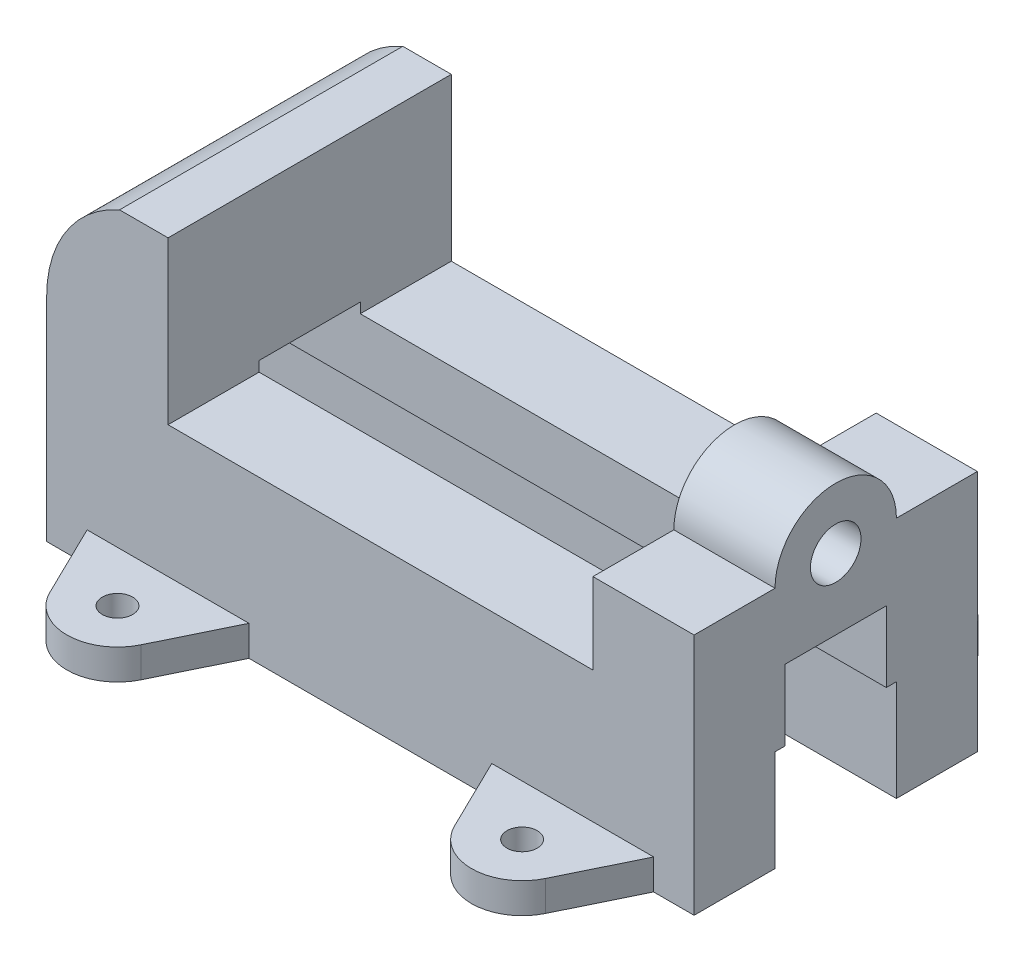
SolidWorks part; units mm, degrees
material "Gray Cast Iron"
ref_plane "Front Plane" through (0, 0, 0) normal (0, 0, 1) x (1, 0, 0)
ref_plane "Top Plane" through (0, 0, 0) normal (0, 1, 0) x (1, 0, 0)
ref_plane "Right Plane" through (0, 0, 0) normal (1, 0, 0) x (0, 0, -1)
sketch "Sketch1" plane through (0, 0, 0) normal (0, 0, 1) x (1, 0, 0)
  line L0 (0, 0) -> (0, 66.675)
  line L1 (0, 0) -> (203.2, 0)
  line L2 (203.2, 0) -> (203.2, 76.2)
  line L3 (203.2, 76.2) -> (171.45, 76.2)
  line L4 (171.45, 76.2) -> (171.45, 50.8)
  line L5 (171.45, 50.8) -> (38.1, 50.8)
  line L7 (38.1, 101.6) -> (38.1, 50.8)
  line L8 (22.8732, 101.6) -> (38.1, 101.6)
  arc A0 (0, 66.675) -> (22.8732, 101.6) centre (38.1, 66.675) cw
  point P10 (38.1, 66.675)
  point P12 (0, 0)
  dimension "D2" = 38.1
  dimension "D1" = 76.2
  dimension "D3" = 50.8
  dimension "D4" = 50.8
  dimension "D5" = 66.675
  dimension "D6" = 133.35
  dimension "D7" = 31.75
extrude "Boss-Extrude1" add sketch "Sketch1" against normal blind 88.9
sketch "Sketch2" plane through (203.2, 0, 0) normal (1, 0, 0) x (0, 0, -1)
  line L0 (88.9, 76.2) -> (0, 76.2) construction
  line L1 (25.4, 76.2) -> (63.5, 76.2)
  arc A0 (63.5, 76.2) -> (25.4, 76.2) centre (44.45, 76.2) ccw
extrude "Boss-Extrude2" add sketch "Sketch2" against normal blind 31.75
sketch "Sketch3" plane through (203.2, 0, 0) normal (1, 0, 0) x (0, 0, -1)
  circle A0 centre (44.45, 76.2) radius 7.9375
  dimension "D1" = 15.875
extrude "Cut-Extrude1" cut sketch "Sketch3" against normal blind 31.75
sketch "Sketch4" plane through (203.2, 0, 0) normal (1, 0, 0) x (0, 0, -1)
  line L0 (63.5, 0) -> (88.9, 0)
  line L1 (88.9, 0) -> (0, 0) construction
  line L4 (25.4, 0) -> (63.5, 0)
  line L5 (63.5, 31.75) -> (60.325, 31.75)
  line L6 (60.325, 31.75) -> (60.325, 53.975)
  line L7 (25.4, 0) -> (25.4, 31.75)
  line L8 (25.4, 31.75) -> (28.575, 31.75)
  line L9 (28.575, 31.75) -> (28.575, 53.975)
  line L10 (28.575, 53.975) -> (60.325, 53.975)
  line L11 (63.5, 31.75) -> (63.5, 0)
  line M14 (0, 0) -> (88.9, 0)
  dimension "D1" = 38.1
  dimension "D2" = 31.75
  dimension "D3" = 31.75
  dimension "D4" = 31.75
  dimension "D5" = 25.4
  dimension "D6" = 3.175
  dimension "D7" = 22.225
extrude "Cut-Extrude2" cut sketch "Sketch4" against normal through all contours L11 L5 L6 L10 L9 L8 L7 M14
sketch "Sketch5" plane through (0, 0, 0) normal (0, 0, 1) x (1, 0, 0)
  line L0 (0, 0) -> (12.7, 0)
  line L1 (0, 0) -> (203.2, 0) construction
  line L2 (12.7, 0) -> (12.7, 9.525)
  line L3 (12.7, 9.525) -> (63.5, 9.525)
  line L4 (63.5, 9.525) -> (63.5, 0)
  line L5 (63.5, 0) -> (12.7, 0)
  line L6 (203.2, 0) -> (190.5, 0)
  line L7 (190.5, 0) -> (190.5, 9.525)
  line L8 (190.5, 9.525) -> (139.7, 9.525)
  line L9 (139.7, 9.525) -> (139.7, 0)
  line L10 (139.7, 0) -> (190.5, 0)
  line L11 (0, 66.675) -> (0, 0) construction
  line M8 (0, 0) -> (203.2, 0)
  dimension "D1" = 12.7
  dimension "D2" = 50.8
  dimension "D3" = 9.525
  dimension "D4" = 9.525
  dimension "D5" = 50.8
  dimension "D6" = 12.7
extrude "Boss-Extrude3" add sketch "Sketch5" along normal blind 15.875 contours L4 L3 L2 M8 | L8 L9 L7 M8
sketch "Sketch7" plane through (0, 9.525, 0) normal (0, 1, 0) x (1, 0, 0)
  line L0 (12.7, -15.875) -> (63.5, -15.875) construction
  line L1 (12.7, 0) -> (23.8303, -22.8315)
  line L2 (63.5, 0) -> (52.3697, -22.8315)
  line L3 (12.7, 0) -> (63.5, 0)
  arc A0 (23.8303, -22.8315) -> (52.3697, -22.8315) centre (38.1, -15.875) ccw
  dimension "D1" = 31.75
extrude "Boss-Extrude4" add sketch "Sketch7" against normal blind 9.525
sketch "Sketch8" plane through (0, 9.525, 0) normal (0, 1, 0) x (1, 0, 0)
  line L0 (12.7, 0) -> (20.4391, -15.875)
  line L1 (20.4391, -15.875) -> (12.7, -15.875)
  line L2 (12.7, -15.875) -> (12.7, 0)
  line L3 (55.7609, -15.875) -> (63.5, 0)
  line L4 (63.5, 0) -> (63.5, -15.875)
  line L5 (63.5, -15.875) -> (55.7609, -15.875)
extrude "Cut-Extrude3" cut sketch "Sketch8" against normal blind 9.525
sketch "Sketch9" plane through (0, 9.525, 0) normal (0, 1, 0) x (1, 0, 0)
  line L0 (190.5, -15.875) -> (139.7, -15.875) construction
  line L1 (139.7, 0) -> (150.8303, -22.8315)
  line L2 (190.5, 0) -> (139.7, 0) construction
  line L3 (190.5, 0) -> (179.3697, -22.8315)
  line L4 (139.7, 0) -> (190.5, 0)
  arc A0 (150.8303, -22.8315) -> (179.3697, -22.8315) centre (165.1, -15.875) ccw
  dimension "D1" = 31.75
extrude "Boss-Extrude5" add sketch "Sketch9" against normal blind 9.525
sketch "Sketch10" plane through (0, 9.525, 0) normal (0, 1, 0) x (1, 0, 0)
  line L0 (147.4391, -15.875) -> (139.7, 0)
  line L1 (139.7, 0) -> (139.7, -15.875)
  line L2 (139.7, -15.875) -> (147.4391, -15.875)
  line L3 (190.5, 0) -> (182.7609, -15.875)
  line L4 (182.7609, -15.875) -> (190.5, -15.875)
  line L5 (190.5, -15.875) -> (190.5, 0)
extrude "Cut-Extrude4" cut sketch "Sketch10" against normal blind 9.525
sketch "Sketch11" plane through (0, 9.525, 0) normal (0, 1, 0) x (1, 0, 0)
  circle A0 centre (38.1, -15.875) radius 4.7625
  dimension "D1" = 9.525
extrude "Cut-Extrude5" cut sketch "Sketch11" against normal through all
sketch "Sketch12" plane through (0, 9.525, 0) normal (0, 1, 0) x (1, 0, 0)
  circle A0 centre (165.1, -15.875) radius 4.7625
  dimension "D1" = 9.525
extrude "Cut-Extrude6" cut sketch "Sketch12" against normal through all
sketch "Sketch13" plane through (0, 0, -88.9) normal (0, 0, -1) x (-1, 0, 0)
  line L0 (-203.2, 0) -> (-190.5, 0)
  line L1 (0, 0) -> (-203.2, 0) construction
  line L2 (-190.5, 0) -> (-190.5, 9.525)
  line L3 (-190.5, 9.525) -> (-139.7, 9.525)
  line L4 (-190.5, 0) -> (-139.7, 0)
  line L5 (-139.7, 0) -> (-139.7, 9.525)
  line L6 (0, 0) -> (-12.7, 0)
  line L7 (-12.7, 0) -> (-12.7, 9.525)
  line L8 (-12.7, 9.525) -> (-63.5, 9.525)
  line L9 (-63.5, 9.525) -> (-63.5, 0)
  line L10 (-63.5, 0) -> (-12.7, 0)
  line M9 (-203.2, 0) -> (0, 0)
  dimension "D1" = 12.7
  dimension "D2" = 12.7
  dimension "D3" = 50.8
  dimension "D4" = 50.8
  dimension "D5" = 9.525
  dimension "D6" = 9.525
extrude "Boss-Extrude6" add sketch "Sketch13" along normal blind 15.875 contours L5 L3 L2 M9 | L8 L9 L7 M9
sketch "Sketch14" plane through (0, 9.525, 0) normal (0, 1, 0) x (1, 0, 0)
  line L0 (190.5, 104.775) -> (139.7, 104.775) construction
  line L1 (190.5, 88.9) -> (179.3697, 111.7315)
  line L2 (139.7, 88.9) -> (150.8303, 111.7315)
  line L3 (190.5, 88.9) -> (139.7, 88.9)
  arc A0 (179.3697, 111.7315) -> (150.8303, 111.7315) centre (165.1, 104.775) ccw
  dimension "D1" = 31.75
extrude "Boss-Extrude7" add sketch "Sketch14" against normal blind 9.525
sketch "Sketch15" plane through (0, 9.525, 0) normal (0, 1, 0) x (1, 0, 0)
  line L0 (182.7609, 104.775) -> (190.5, 88.9)
  line L1 (190.5, 88.9) -> (190.5, 104.775)
  line L2 (190.5, 104.775) -> (182.7609, 104.775)
  line L3 (147.4391, 104.775) -> (139.7, 88.9)
  line L4 (139.7, 88.9) -> (139.7, 104.775)
  line L5 (139.7, 104.775) -> (147.4391, 104.775)
extrude "Cut-Extrude7" cut sketch "Sketch15" against normal blind 9.525
sketch "Sketch16" plane through (0, 9.525, 0) normal (0, 1, 0) x (1, 0, 0)
  line L0 (12.7, 104.775) -> (63.5, 104.775) construction
  line L1 (63.5, 88.9) -> (52.3697, 111.7315)
  line L2 (12.7, 88.9) -> (23.8303, 111.7315)
  line L3 (63.5, 88.9) -> (12.7, 88.9)
  arc A0 (52.3697, 111.7315) -> (23.8303, 111.7315) centre (38.1, 104.775) ccw
  dimension "D1" = 31.75
extrude "Boss-Extrude8" add sketch "Sketch16" against normal blind 9.525
sketch "Sketch17" plane through (0, 9.525, 0) normal (0, 1, 0) x (1, 0, 0)
  line L0 (63.5, 88.9) -> (55.7609, 104.775)
  line L1 (55.7609, 104.775) -> (63.5, 104.775)
  line L2 (63.5, 104.775) -> (63.5, 88.9)
  line L3 (12.7, 88.9) -> (12.7, 104.775)
  line L4 (12.7, 104.775) -> (20.4391, 104.775)
  line L5 (20.4391, 104.775) -> (12.7, 88.9)
extrude "Cut-Extrude8" cut sketch "Sketch17" against normal blind 9.525
sketch "Sketch18" plane through (0, 9.525, 0) normal (0, 1, 0) x (1, 0, 0)
  circle A0 centre (165.1, 104.775) radius 4.7625
  circle A1 centre (38.1, 104.775) radius 4.7625
  dimension "D1" = 9.525
extrude "Cut-Extrude9" cut sketch "Sketch18" against normal through all
